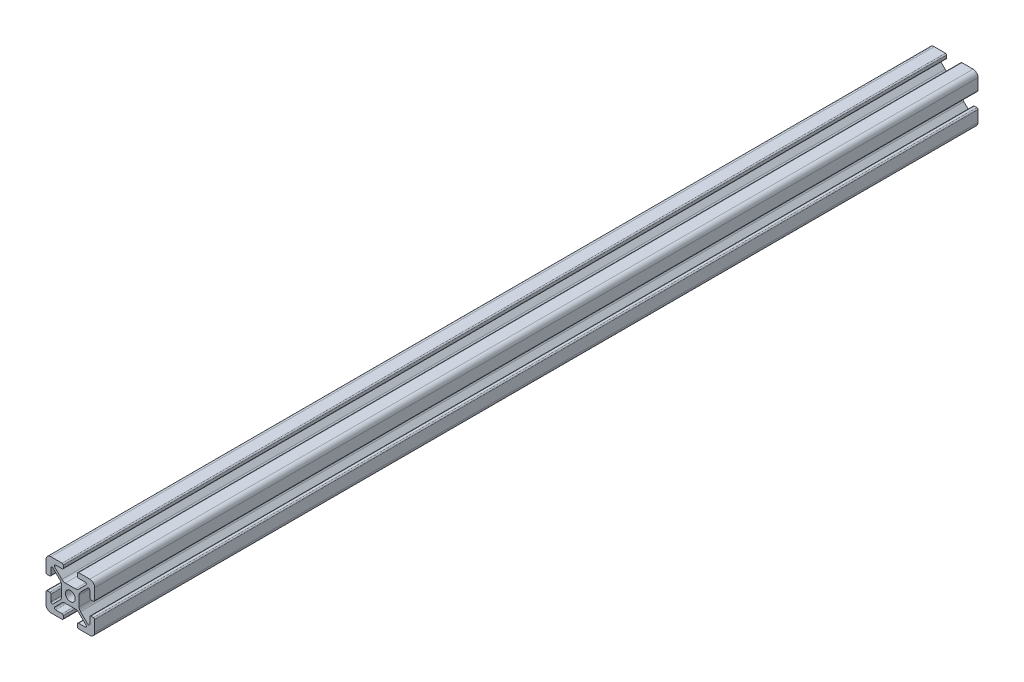
SolidWorks part; units mm, degrees
ref_plane "Front Plane" through (0, 0, 0) normal (0, 0, 1) x (1, 0, 0)
ref_plane "Top Plane" through (0, 0, 0) normal (0, 1, 0) x (1, 0, 0)
ref_plane "Right Plane" through (0, 0, 0) normal (1, 0, 0) x (0, 0, -1)
sketch "Sketch1" plane through (0, 0, 0) normal (0, 0, 1) x (1, 0, 0)
  line L0 (4.4179, 5.3159) -> (8.178, 9.076)
  line L1 (-10.16, -12.7) -> (-4.309, -12.7)
  line L2 (-12.7, -10.16) -> (-12.7, -4.309)
  line L3 (-10.16, 12.7) -> (-4.309, 12.7)
  line L4 (12.7, -10.16) -> (12.7, -4.309)
  line L5 (-12.7, -12.7) -> (12.7, 12.7) construction
  line L6 (-12.7, 12.7) -> (12.7, -12.7) construction
  line L7 (-2.6219, -4.572) -> (2.6219, -4.572)
  line L8 (-4.572, -2.6219) -> (-4.572, 2.6219)
  line L9 (-2.6219, 4.572) -> (2.6219, 4.572)
  line L10 (4.572, -2.6219) -> (4.572, 2.6219)
  line L11 (-4.572, -4.572) -> (4.572, 4.572) construction
  line L12 (-4.572, 4.572) -> (4.572, -4.572) construction
  line L13 (5.3159, 4.4179) -> (9.076, 8.178)
  line L14 (5.3159, -4.4179) -> (9.076, -8.178)
  line L15 (4.4179, -5.3159) -> (8.178, -9.076)
  line L16 (-4.4179, -5.3159) -> (-8.178, -9.076)
  line L17 (-5.3159, -4.4179) -> (-9.076, -8.178)
  line L18 (-5.3159, 4.4179) -> (-9.076, 8.178)
  line L19 (-4.4179, 5.3159) -> (-8.178, 9.076)
  line L20 (-3.674, 4.572) -> (-3.8683, 4.7663) construction
  line L21 (-10.16, 10.16) -> (10.16, 10.16) construction
  line L22 (-7.7289, 10.16) -> (-4.309, 10.16)
  line L23 (10.16, -7.7289) -> (10.16, -4.309)
  line L24 (-7.7289, -10.16) -> (-4.309, -10.16)
  line L25 (-10.16, -7.7289) -> (-10.16, -4.309)
  line L26 (-10.16, -10.16) -> (-10.16, 10.16) construction
  line L27 (-10.16, -10.16) -> (10.16, -10.16) construction
  line L28 (10.16, -10.16) -> (10.16, 10.16) construction
  line L29 (-4.572, 3.674) -> (-17.3082, 3.674) construction
  line L30 (-4.572, -3.674) -> (-17.7261, -3.674) construction
  line L31 (-17.7261, -3.674) -> (20.6347, -3.674) construction
  line L32 (-4.572, 3.674) -> (19.3811, 3.674) construction
  line L33 (-12.7, 4.309) -> (-12.7, 10.16)
  line L34 (-10.16, 4.309) -> (-10.16, 7.7289)
  line L35 (-12.7, -12.7) -> (-12.7, 12.7) construction
  line L36 (12.7, 4.309) -> (12.7, 10.16)
  line L37 (10.16, 4.309) -> (10.16, 7.7289)
  line L38 (12.7, -12.7) -> (12.7, 12.7) construction
  line L39 (-3.674, 10.795) -> (-3.674, 12.065)
  line L40 (3.674, 10.795) -> (3.674, 12.065)
  line L41 (-3.674, -10.795) -> (-3.674, -12.065)
  line L42 (3.674, -10.795) -> (3.674, -12.065)
  line L43 (4.309, -10.16) -> (7.7289, -10.16)
  line L44 (4.309, -12.7) -> (10.16, -12.7)
  line L45 (4.309, 12.7) -> (10.16, 12.7)
  line L46 (-12.7, -12.7) -> (12.7, -12.7) construction
  line L47 (4.309, 10.16) -> (7.7289, 10.16)
  line L48 (-12.7, 12.7) -> (12.7, 12.7) construction
  line L49 (-12.065, 3.674) -> (-10.795, 3.674)
  line L50 (-12.065, -3.674) -> (-10.795, -3.674)
  line L51 (10.795, -3.674) -> (12.065, -3.674)
  line L52 (12.065, 3.674) -> (10.795, 3.674)
  circle A0 centre (0, 0) radius 2.54
  arc A1 (5.3159, -4.4179) -> (4.572, -2.6219) centre (7.112, -2.6219) cw
  arc A2 (5.3159, 4.4179) -> (4.572, 2.6219) centre (7.112, 2.6219) ccw
  arc A3 (4.4179, 5.3159) -> (2.6219, 4.572) centre (2.6219, 7.112) cw
  arc A4 (-4.4179, 5.3159) -> (-2.6219, 4.572) centre (-2.6219, 7.112) ccw
  arc A5 (-5.3159, 4.4179) -> (-4.572, 2.6219) centre (-7.112, 2.6219) cw
  arc A6 (-5.3159, -4.4179) -> (-4.572, -2.6219) centre (-7.112, -2.6219) ccw
  arc A7 (4.4179, -5.3159) -> (2.6219, -4.572) centre (2.6219, -7.112) ccw
  arc A8 (-4.4179, -5.3159) -> (-2.6219, -4.572) centre (-2.6219, -7.112) cw
  arc A9 (-10.16, -12.7) -> (-12.7, -10.16) centre (-10.16, -10.16) cw
  arc A10 (10.16, -12.7) -> (12.7, -10.16) centre (10.16, -10.16) ccw
  arc A11 (10.16, 12.7) -> (12.7, 10.16) centre (10.16, 10.16) cw
  arc A12 (-12.7, 10.16) -> (-10.16, 12.7) centre (-10.16, 10.16) cw
  arc A13 (-7.7289, -10.16) -> (-8.178, -9.076) centre (-7.7289, -9.525) cw
  arc A14 (-10.16, -7.7289) -> (-9.076, -8.178) centre (-9.525, -7.7289) ccw
  arc A15 (10.16, -7.7289) -> (9.076, -8.178) centre (9.525, -7.7289) cw
  arc A16 (8.178, -9.076) -> (7.7289, -10.16) centre (7.7289, -9.525) cw
  arc A17 (9.076, 8.178) -> (10.16, 7.7289) centre (9.525, 7.7289) cw
  arc A18 (8.178, 9.076) -> (7.7289, 10.16) centre (7.7289, 9.525) ccw
  arc A19 (-7.7289, 10.16) -> (-8.178, 9.076) centre (-7.7289, 9.525) ccw
  arc A20 (-9.076, 8.178) -> (-10.16, 7.7289) centre (-9.525, 7.7289) ccw
  arc A21 (-10.16, -4.309) -> (-10.795, -3.674) centre (-10.795, -4.309) ccw
  arc A22 (-12.7, -4.309) -> (-12.065, -3.674) centre (-12.065, -4.309) cw
  arc A23 (-3.674, -12.065) -> (-4.309, -12.7) centre (-4.309, -12.065) cw
  arc A24 (-3.674, -10.795) -> (-4.309, -10.16) centre (-4.309, -10.795) ccw
  arc A25 (3.674, -10.795) -> (4.309, -10.16) centre (4.309, -10.795) cw
  arc A26 (3.674, -12.065) -> (4.309, -12.7) centre (4.309, -12.065) ccw
  arc A27 (10.16, -4.309) -> (10.795, -3.674) centre (10.795, -4.309) cw
  arc A28 (12.7, -4.309) -> (12.065, -3.674) centre (12.065, -4.309) ccw
  arc A29 (10.16, 4.309) -> (10.795, 3.674) centre (10.795, 4.309) ccw
  arc A30 (12.7, 4.309) -> (12.065, 3.674) centre (12.065, 4.309) cw
  arc A31 (4.309, 10.16) -> (3.674, 10.795) centre (4.309, 10.795) cw
  arc A32 (3.674, 12.065) -> (4.309, 12.7) centre (4.309, 12.065) cw
  arc A33 (-4.309, 10.16) -> (-3.674, 10.795) centre (-4.309, 10.795) ccw
  arc A34 (-3.674, 12.065) -> (-4.309, 12.7) centre (-4.309, 12.065) ccw
  arc A35 (-12.7, 4.309) -> (-12.065, 3.674) centre (-12.065, 4.309) ccw
  arc A36 (-10.16, 4.309) -> (-10.795, 3.674) centre (-10.795, 4.309) cw
  point P0 (0, 0)
  point P16 (1.8779, 6.3681)
  point P17 (12.7565, 17.2467)
  point P18 (2.7759, 5.47)
  point P20 (4.572, -3.674)
  point P28 (4.572, 3.674)
  point P31 (0, 0)
  point P32 (13.6546, 16.3486)
  point P66 (3.674, 4.572)
  point P110 (-10.16, -3.674)
  point P113 (-12.7, -3.674)
  point P120 (3.674, -10.16)
  point P123 (3.674, -12.7)
  point P126 (10.16, -3.674)
  point P129 (12.7, -3.674)
  point P132 (10.16, 3.674)
  point P135 (12.7, 3.674)
  point P140 (3.674, 12.7)
  point P147 (-12.7, 3.674)
  point P150 (-10.16, 3.674)
  dimension "D3" = 5.08
  dimension "D8" = 2.54
  dimension "D9" = 0.635
  dimension "D10" = 0.635
  dimension "D1" = 25.4
  dimension "D2" = 25.4
  dimension "D4" = 9.144
  dimension "D5" = 1.27
  dimension "D7" = 2.54
  dimension "D6" = 4
extrude "Boss-Extrude1" add sketch "Sketch1" along normal blind 461.264
